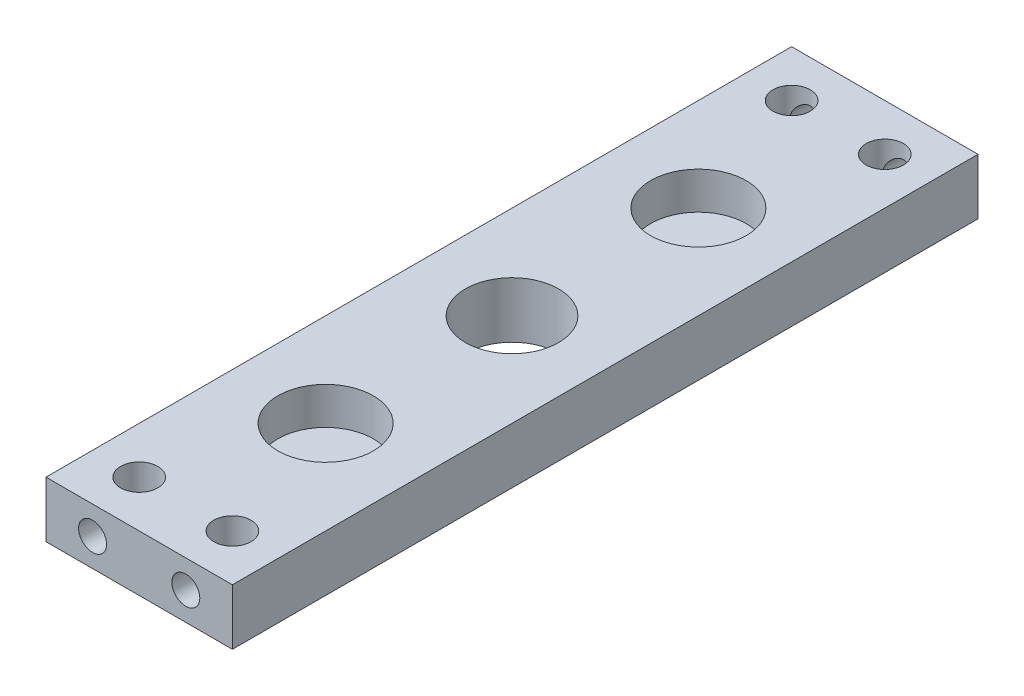
SolidWorks part; units mm, degrees
material "Beech"
ref_plane "Front Plane" through (0, 0, 0) normal (0, 0, 1) x (1, 0, 0)
ref_plane "Top Plane" through (0, 0, 0) normal (0, 1, 0) x (1, 0, 0)
ref_plane "Right Plane" through (0, 0, 0) normal (1, 0, 0) x (0, 0, -1)
sketch "Sketch1" plane through (0, 0, 0) normal (0, 1, 0) x (1, 0, 0)
  line L1 (20, -80) -> (-20, -80)
  line L2 (20, -80) -> (20, 80)
  line L3 (20, 80) -> (-20, 80)
  line L4 (-20, -80) -> (-20, 80)
  line L5 (20, -80) -> (-20, 80) construction
  line L6 (20, 80) -> (-20, -80) construction
  circle A0 centre (0, 0) radius 10
  dimension "D1" = 20
  dimension "D6" = 40
  dimension "D7" = 160
extrude "Boss-Extrude1" add sketch "Sketch1" along normal blind 12
sketch "Sketch4" plane through (0, 12, 0) normal (0, 1, 0) x (1, 0, 0)
  line L0 (-40.443, 70) -> (34.6927, 70) construction
  line L1 (-20, 80) -> (-20, -80) construction
  line L2 (20, -80) -> (20, 80) construction
  line L3 (20, 80) -> (-20, 80) construction
  circle A0 centre (-10, 70) radius 4
  circle A1 centre (10, 70) radius 4
  dimension "D1" = 8
  dimension "D2" = 8
  dimension "D3" = 10
  dimension "D4" = 10
  dimension "D5" = 10
extrude "Cut-Extrude3" cut sketch "Sketch4" against normal up to next
sketch "Sketch5" plane through (0, 0, -80) normal (0, 0, -1) x (-1, 0, 0)
  line L0 (33.3705, 6) -> (-34.1913, 6) construction
  line L1 (20, 12) -> (20, 0) construction
  line L2 (-20, 12) -> (-20, 0) construction
  circle A0 centre (10, 6) radius 3
  circle A1 centre (-10, 6) radius 3
  dimension "D1" = 6
  dimension "D2" = 10
  dimension "D3" = 6
  dimension "D4" = 10
extrude "Cut-Extrude4" cut sketch "Sketch5" against normal up to next
mirror "Mirror1" about plane through (0, 0, 0) normal (0, 0, 1) of "Cut-Extrude3", "Cut-Extrude4"
sketch "Sketch6" plane through (0, 12, 0) normal (0, 1, 0) x (1, 0, 0)
  line L0 (0, -38.7759) -> (0, 46.8008) construction
  circle A0 centre (0, 40) radius 10.25
  circle A1 centre (0, -40) radius 10.25
  circle A2 centre (0, 0) radius 10 construction
  dimension "D1" = 20.5
  dimension "D2" = 20.5
  dimension "D3" = 40
  dimension "D4" = 40
extrude "Cut-Extrude5" cut sketch "Sketch6" against normal blind 8
